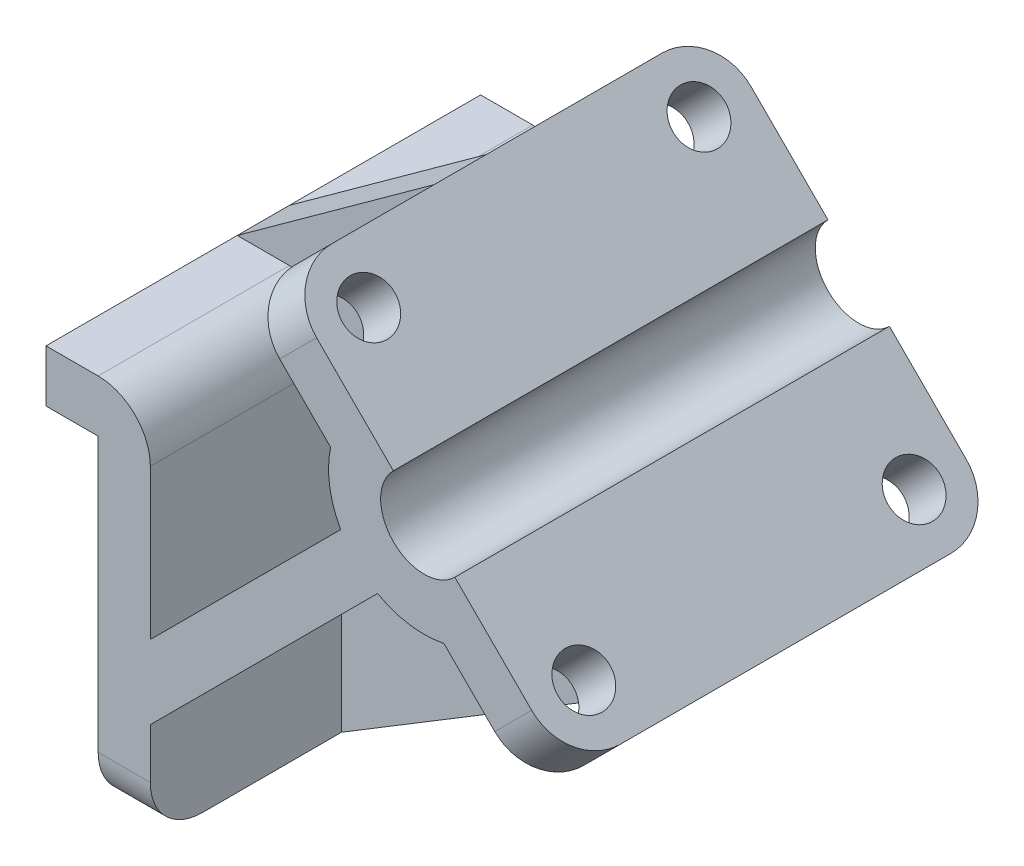
SolidWorks part; units mm, degrees
ref_plane "Front Plane" through (0, 0, 0) normal (0, 0, 1) x (1, 0, 0)
ref_plane "Top Plane" through (0, 0, 0) normal (0, 1, 0) x (1, 0, 0)
ref_plane "Right Plane" through (0, 0, 0) normal (1, 0, 0) x (0, 0, -1)
sketch "Sketch1" plane through (0, 0, 0) normal (0, 0, 1) x (1, 0, 0)
  line L0 (0, 0) -> (-12, 0)
  line L1 (-12, 0) -> (-12, 75)
  line L2 (-12, 75) -> (-24, 75)
  line L3 (-24, 75) -> (-24, 87)
  line L4 (-24, 87) -> (-12, 87)
  line L5 (0, 0) -> (0, 23.5147)
  line L6 (0, 40.4853) -> (43.7907, 84.276)
  line L7 (0, 23.5147) -> (52.276, 75.7907)
  line L8 (21.2807, 119.7487) -> (41.4763, 99.5531)
  line L9 (87.7487, 53.2807) -> (96.234, 61.766)
  line L10 (96.234, 61.766) -> (70.0711, 87.9289)
  line L11 (29.766, 128.234) -> (21.2807, 119.7487)
  line L12 (0, 32) -> (63, 95) construction
  line L13 (55.9289, 102.0711) -> (29.766, 128.234)
  line L14 (67.5531, 73.4763) -> (87.7487, 53.2807)
  line L15 (0, 40.4853) -> (0, 75)
  arc A0 (0, 75) -> (-12, 87) centre (-12, 75) ccw
  arc A1 (55.9289, 102.0711) -> (70.0711, 87.9289) centre (63, 95) ccw
  arc A2 (41.4763, 99.5531) -> (43.7907, 84.276) centre (63, 95) ccw
  arc A3 (52.276, 75.7907) -> (67.5531, 73.4763) centre (63, 95) ccw
  point P20 (0, 0)
  point P22 (0, 0)
  point P23 (0, 0)
  point P24 (0, 0)
  point P25 (0, 0)
  point P26 (0, 0)
  point P27 (0, 0)
  point P28 (0, 0)
  dimension "D6" = 12
  dimension "D11" = 94
  dimension "D15" = 20
  dimension "D16" = 44
  dimension "D1" = 12
  dimension "D2" = 135
  dimension "D3" = 12
  dimension "D4" = 75
  dimension "D5" = 75
  dimension "D7" = 12
  dimension "D8" = 6
  dimension "D9" = 20
  dimension "D10" = 75
  dimension "D12" = 37
  dimension "D13" = 12
  dimension "D14" = 90
extrude "Boss-Extrude1" add sketch "Sketch1" along normal mid plane 100
sketch "Sketch2" plane through (79, 79, 0) normal (0.7071, 0.7071, 0) x (0, 0, -1)
  line L0 (-50, 32.6274) -> (-50, 69.6274) construction
  line L1 (-50, 69.6274) -> (50, 69.6274) construction
  line L2 (50, 32.6274) -> (50, 69.6274) construction
  line L3 (50, -24.3726) -> (50, 12.6274) construction
  line L4 (-50, -24.3726) -> (50, -24.3726) construction
  line L5 (-50, -24.3726) -> (-50, 12.6274) construction
  circle A0 centre (-38, 57.6274) radius 6
  circle A1 centre (38, 57.6274) radius 6
  circle A2 centre (38, -12.3726) radius 6
  circle A3 centre (-38, -12.3726) radius 6
  dimension "D1" = 12
  dimension "D2" = 12
  dimension "D3" = 12
  dimension "D4" = 12
  dimension "D5" = 12
  dimension "D6" = 12
  dimension "D7" = 12
  dimension "D8" = 12
  dimension "D9" = 12
  dimension "D10" = 12
  dimension "D11" = 12
  dimension "D12" = 12
extrude "Cut-Extrude1" cut sketch "Sketch2" against normal blind 12
fillet "Fillet1" radius 12 4 edges at (25.5233, 123.9914, -50) (91.9914, 57.5233, -50) (91.9914, 57.5233, 50) (25.5233, 123.9914, 50)
fillet "Fillet2" radius 12 2 edges at (-6, 0, -50) (-6, 0, 50)
sketch "Sketch14" plane through (0, 0, 0) normal (0, 0, 1) x (1, 0, 0)
  line L0 (21.2807, 119.7487) -> (-24, 87)
rib "Rib3" sketch "Sketch14" sketch "Sketch14" thickness 12 extrusion direction parallel to sketch draft on no parameters "D1"=12
sketch "Sketch15" plane through (0, 0, 0) normal (0, 0, 1) x (1, 0, 0)
  line L0 (87.7487, 53.2807) -> (0, 0)
rib "Rib5" sketch "Sketch15" sketch "Sketch15" thickness 12 extrusion direction parallel to sketch draft on no parameters "D1"=12
